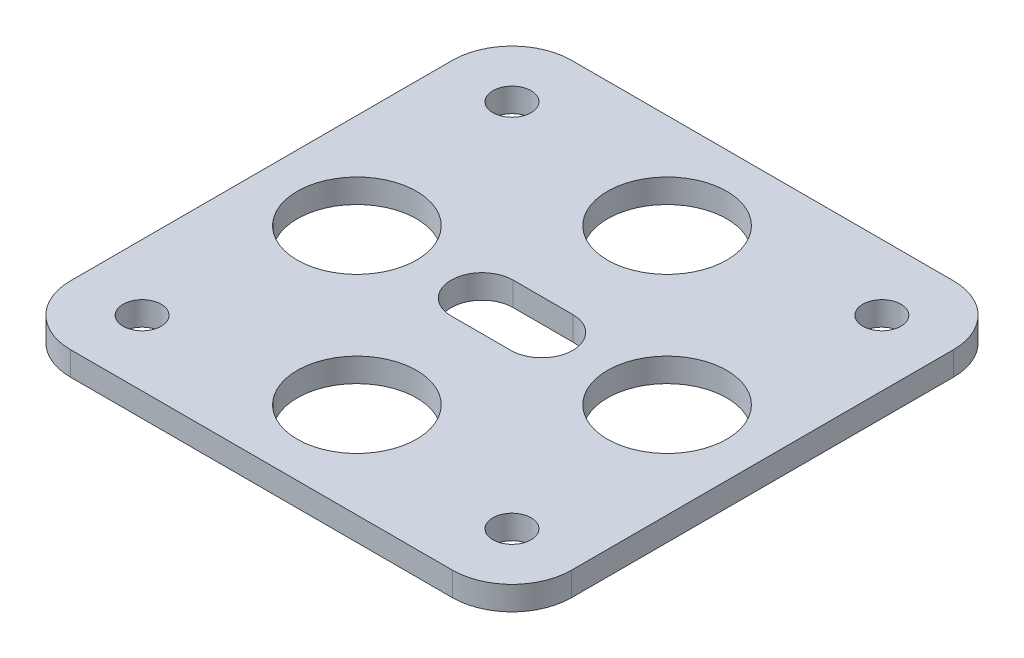
SolidWorks part; units mm, degrees
ref_plane "Front Plane" through (0, 0, 0) normal (0, 0, 1) x (1, 0, 0)
ref_plane "Top Plane" through (0, 0, 0) normal (0, 1, 0) x (1, 0, 0)
ref_plane "Right Plane" through (0, 0, 0) normal (1, 0, 0) x (0, 0, -1)
sketch "Sketch1" plane through (0, 0, 0) normal (0, 1, 0) x (1, 0, 0)
  line L0 (0, 21) -> (0, -21) construction
  line L1 (-21, -21) -> (21, -21)
  line L2 (-21, -21) -> (-21, 21)
  line L3 (-21, 21) -> (21, 21)
  line L4 (21, -21) -> (21, 21)
  line L5 (-21, -21) -> (21, 21) construction
  line L6 (-21, 21) -> (21, -21) construction
  line L7 (-21, 0) -> (21, 0) construction
  line L8 (-2.5, 0) -> (2.5, 0) construction
  line L9 (-2.5, 2.6) -> (2.5, 2.6)
  line L10 (-2.5, -2.6) -> (2.5, -2.6)
  circle A0 centre (15.5, 15.5) radius 1.6
  circle A1 centre (-15.5, 15.5) radius 1.6
  circle A2 centre (15.5, -15.5) radius 1.6
  circle A3 centre (-15.5, -15.5) radius 1.6
  arc A4 (-2.5, 2.6) -> (-2.5, -2.6) centre (-2.5, 0) ccw
  arc A5 (2.5, -2.6) -> (2.5, 2.6) centre (2.5, 0) ccw
  circle A6 centre (0, 13) radius 5
  circle A7 centre (13, 0) radius 5
  circle A8 centre (0, -13) radius 5
  circle A9 centre (-13, 0) radius 5
  point P0 (0, 0)
  point P20 (0, 0)
  point P36 (0, 0)
  dimension "D3" = 3.2
  dimension "D4" = 31
  dimension "D5" = 2.6
  dimension "D7" = 10
  dimension "D8" = 8
  dimension "D1" = 42
  dimension "D2" = 42
  dimension "D6" = 5
  dimension "D9" = 4
extrude "Boss-Extrude1" add sketch "Sketch1" along normal blind 2
fillet "Fillet1" radius 5 4 edges at (-21, 1, -21) (21, 1, -21) (21, 1, 21) (-21, 1, 21)
